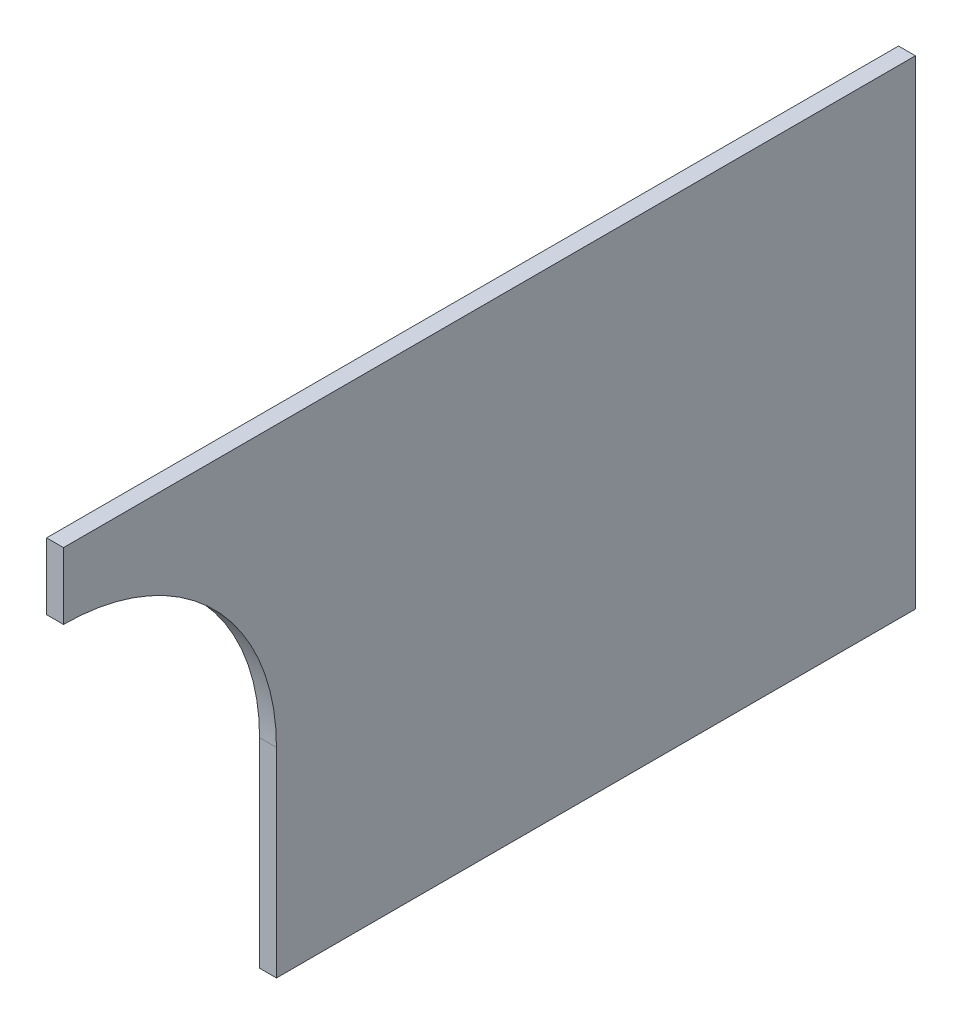
SolidWorks part; units mm, degrees
material "PE High Density"
ref_plane "Front Plane" through (0, 0, 0) normal (0, 0, 1) x (1, 0, 0)
ref_plane "Top Plane" through (0, 0, 0) normal (0, 1, 0) x (1, 0, 0)
ref_plane "Right Plane" through (0, 0, 0) normal (1, 0, 0) x (0, 0, -1)
sketch "Sketch1" plane through (0, 0, 0) normal (1, 0, 0) x (0, 0, -1)
  line L0 (0, 0) -> (0, 75)
  line L1 (-80, 155) -> (-138.0002, 155) construction
  line L2 (-80, 155) -> (-80, 180)
  line L3 (-80, 180) -> (240, 180)
  line L4 (240, 180) -> (240, 0)
  line L5 (240, 0) -> (0, 0)
  arc A0 (0, 75) -> (-80, 155) centre (-80, 75) ccw
  dimension "D1" = 320
  dimension "D2" = 180
  dimension "D3" = 25
  dimension "D4" = 240
extrude "Boss-Extrude1" add sketch "Sketch1" along normal blind 6.35
